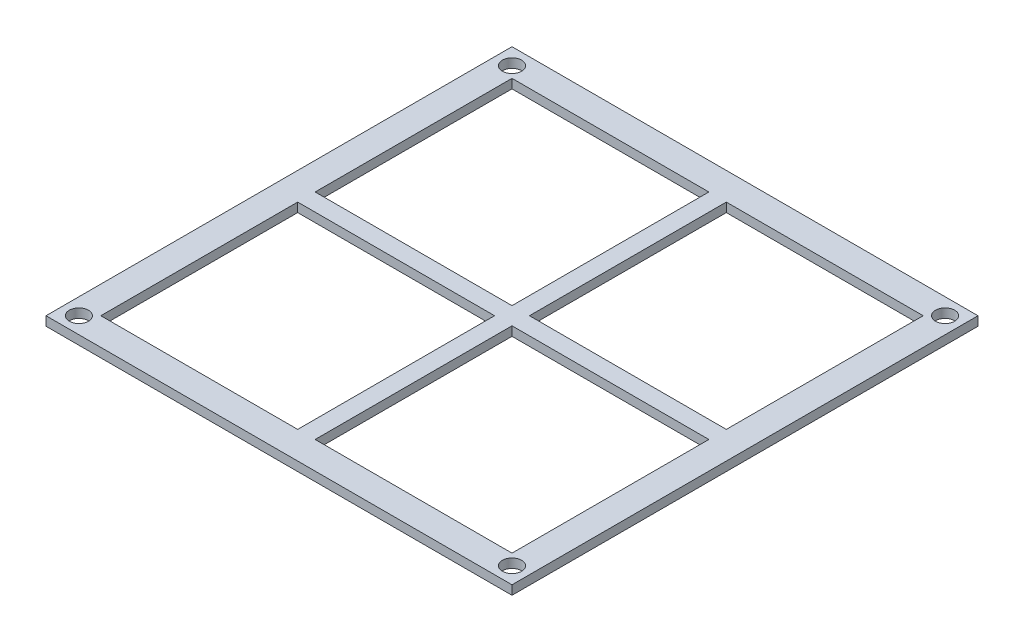
SolidWorks part; units mm, degrees
ref_plane "Front Plane" through (0, 0, 0) normal (0, 0, 1) x (1, 0, 0)
ref_plane "Top Plane" through (0, 0, 0) normal (0, 1, 0) x (1, 0, 0)
ref_plane "Right Plane" through (0, 0, 0) normal (1, 0, 0) x (0, 0, -1)
sketch "Sketch1" plane through (0, 0, 0) normal (0, 1, 0) x (1, 0, 0)
  line L1 (60.198, -60.198) -> (-60.198, -60.198) construction
  line L2 (60.198, -60.198) -> (60.198, 60.198) construction
  line L3 (60.198, 60.198) -> (-60.198, 60.198) construction
  line L4 (-60.198, -60.198) -> (-60.198, 60.198) construction
  line L5 (60.198, -60.198) -> (-60.198, 60.198) construction
  line L6 (60.198, 60.198) -> (-60.198, -60.198) construction
  line L7 (-76.2, -76.2) -> (76.2, -76.2) construction
  line L8 (-76.2, -76.2) -> (-76.2, 76.2) construction
  line L9 (-76.2, 76.2) -> (76.2, 76.2) construction
  line L10 (76.2, -76.2) -> (76.2, 76.2) construction
  line L11 (-76.2, -76.2) -> (76.2, 76.2) construction
  line L12 (-76.2, 76.2) -> (76.2, -76.2) construction
  line L13 (57.15, -57.15) -> (-57.15, -57.15)
  line L14 (57.15, -57.15) -> (57.15, 57.15)
  line L15 (57.15, 57.15) -> (-57.15, 57.15)
  line L16 (-57.15, -57.15) -> (-57.15, 57.15)
  line L17 (57.15, -57.15) -> (-57.15, 57.15) construction
  line L18 (57.15, 57.15) -> (-57.15, -57.15) construction
  line L19 (64.77, -64.77) -> (-64.77, -64.77)
  line L20 (64.77, -64.77) -> (64.77, 64.77)
  line L21 (64.77, 64.77) -> (-64.77, 64.77)
  line L22 (-64.77, -64.77) -> (-64.77, 64.77)
  line L23 (64.77, -64.77) -> (-64.77, 64.77) construction
  line L24 (64.77, 64.77) -> (-64.77, -64.77) construction
  line L25 (64.77, -2.4263) -> (-64.77, -2.4263)
  line L26 (64.77, -2.4263) -> (64.77, 2.4263)
  line L27 (64.77, 2.4263) -> (-64.77, 2.4263)
  line L28 (-64.77, -2.4263) -> (-64.77, 2.4263)
  line L29 (64.77, -2.4263) -> (-64.77, 2.4263) construction
  line L30 (64.77, 2.4263) -> (-64.77, -2.4263) construction
  line L31 (-2.4263, -64.77) -> (2.4263, -64.77)
  line L32 (-2.4263, -64.77) -> (-2.4263, 64.77)
  line L33 (-2.4263, 64.77) -> (2.4263, 64.77)
  line L34 (2.4263, -64.77) -> (2.4263, 64.77)
  line L35 (-2.4263, -64.77) -> (2.4263, 64.77) construction
  line L36 (-2.4263, 64.77) -> (2.4263, -64.77) construction
  circle A0 centre (-60.198, -60.198) radius 2.667
  circle A1 centre (60.198, -60.198) radius 2.667
  circle A2 centre (-60.198, 60.198) radius 2.667
  circle A3 centre (60.198, 60.198) radius 2.667
  point P0 (0, 0)
  point P10 (0, 0)
  point P15 (0, 0)
  point P20 (0, 0)
  point P25 (0, 0)
  point P30 (0, 0)
  dimension "D3" = 5.334
  dimension "D4" = 5.334
  dimension "D5" = 5.334
  dimension "D6" = 5.334
  dimension "D1" = 120.396
  dimension "D2" = 120.396
  dimension "D7" = 152.4
  dimension "D8" = 152.4
  dimension "D9" = 129.54
  dimension "D10" = 114.3
extrude "Boss-Extrude1" add sketch "Sketch1" along normal blind 2.54 contours L34 L19 L20 L25 L14 L13 A1 | L19 L32 L13 L16 L25 L22 A0 | L13 L34 L25 L32 | L25 L32 L27 L16 | L34 L25 L14 L27 | L20 L27 L14 L25 | L34 L15 L14 L27 L20 L21 A3 | L15 L32 L21 L22 L27 L16 A2 | L16 L27 L22 L25
